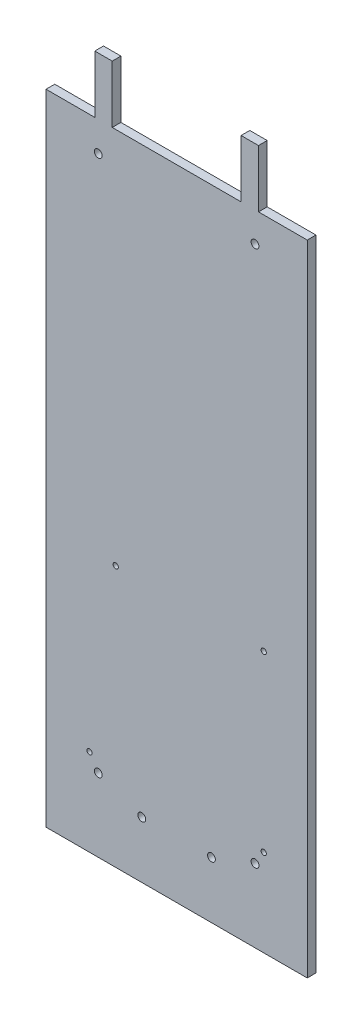
SolidWorks part; units mm, degrees
ref_plane "前视基准面" through (0, 0, 0) normal (0, 0, 1) x (1, 0, 0)
ref_plane "上视基准面" through (0, 0, 0) normal (0, 1, 0) x (1, 0, 0)
ref_plane "右视基准面" through (0, 0, 0) normal (1, 0, 0) x (0, 0, -1)
sketch "草图1" plane through (0, 0, 0) normal (0, 0, 1) x (1, 0, 0)
  line L0 (75, 425.9559) -> (75, -53.0632) construction
  line L1 (0, 0) -> (150, 0)
  line L2 (0, 0) -> (0, 367)
  line L3 (28, 400) -> (38, 400)
  line L4 (150, 0) -> (150, 367)
  line L5 (38, 400) -> (38, 367)
  line L6 (38, 367) -> (75, 367)
  line L7 (28, 400) -> (28, 367)
  line L8 (28, 367) -> (0, 367)
  line L9 (112, 400) -> (122, 400)
  line L10 (75, 367) -> (112, 367)
  line L11 (112, 367) -> (112, 400)
  line L12 (122, 400) -> (122, 367)
  line L13 (122, 367) -> (150, 367)
  circle A0 centre (30, 42) radius 2.25
  circle A1 centre (120, 42) radius 2.25
  circle A4 centre (30, 350) radius 2.25
  circle A5 centre (120, 350) radius 2.25
  circle A6 centre (25, 50) radius 1.5
  circle A7 centre (125, 50) radius 1.5
  circle A8 centre (40, 150) radius 1.5
  circle A9 centre (125, 150) radius 1.5
  circle A10 centre (55, 32.5) radius 2.25
  circle A11 centre (95, 32.5) radius 2.25
  dimension "D4" = 4.5
  dimension "D5" = 45
  dimension "D7" = 42
  dimension "D8" = 42
  dimension "D9" = 3
  dimension "D10" = 50
  dimension "D11" = 50
  dimension "D12" = 3
  dimension "D13" = 50
  dimension "D14" = 50
  dimension "D15" = 45
  dimension "D16" = 45
  dimension "D17" = 50
  dimension "D18" = 50
  dimension "D19" = 3
  dimension "D20" = 3
  dimension "D21" = 35
  dimension "D22" = 50
  dimension "D23" = 100
  dimension "D24" = 100
  dimension "D26" = 4.5
  dimension "D25" = 32.5
  dimension "D27" = 4.5
  dimension "D28" = 32.5
  dimension "D29" = 20
  dimension "D30" = 20
  dimension "D31" = 4.5
  dimension "D32" = 37
  dimension "D3" = 75
  dimension "D6" = 45
  dimension "D33" = 47
  dimension "D34" = 37
  dimension "D35" = 47
  dimension "D36" = 33
  dimension "D37" = 400
  dimension "D38" = 150
extrude "凸台-拉伸1" add sketch "草图1" along normal blind 5
